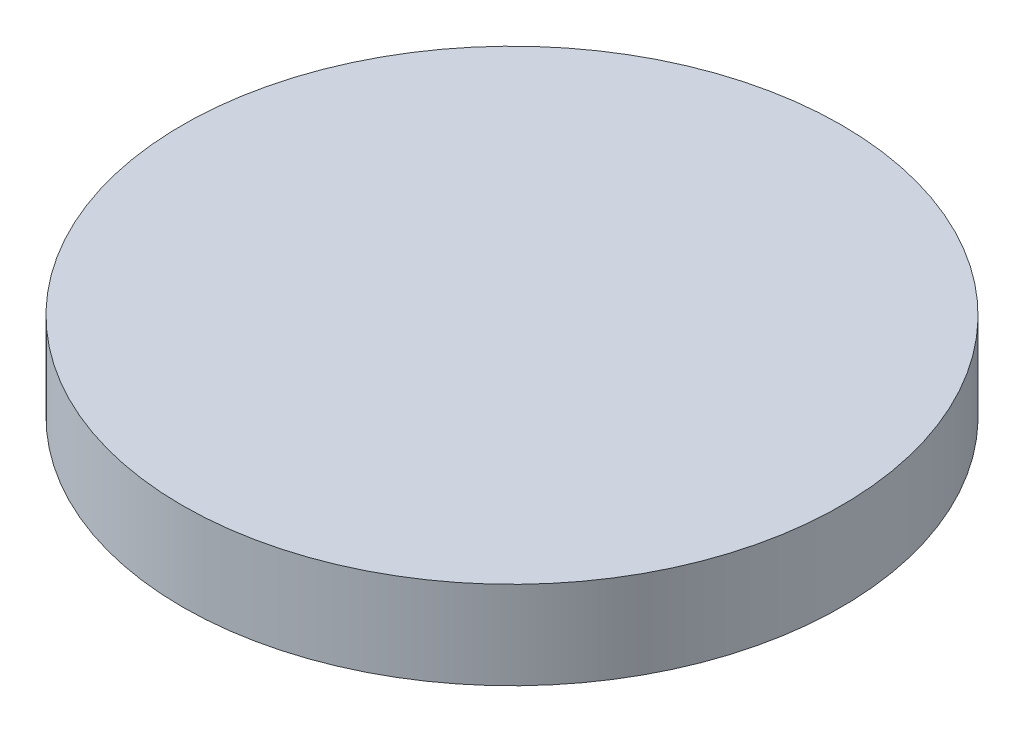
SolidWorks part; units mm, degrees
ref_plane "Front Plane" through (0, 0, 0) normal (0, 0, 1) x (1, 0, 0)
ref_plane "Top Plane" through (0, 0, 0) normal (0, 1, 0) x (1, 0, 0)
ref_plane "Right Plane" through (0, 0, 0) normal (1, 0, 0) x (0, 0, -1)
sketch "Sketch1" plane through (0, 0, 0) normal (0, 1, 0) x (1, 0, 0)
  circle A0 centre (0, 0) radius 19.05
extrude "Boss-Extrude1" add sketch "Sketch1" along normal blind 5.08
